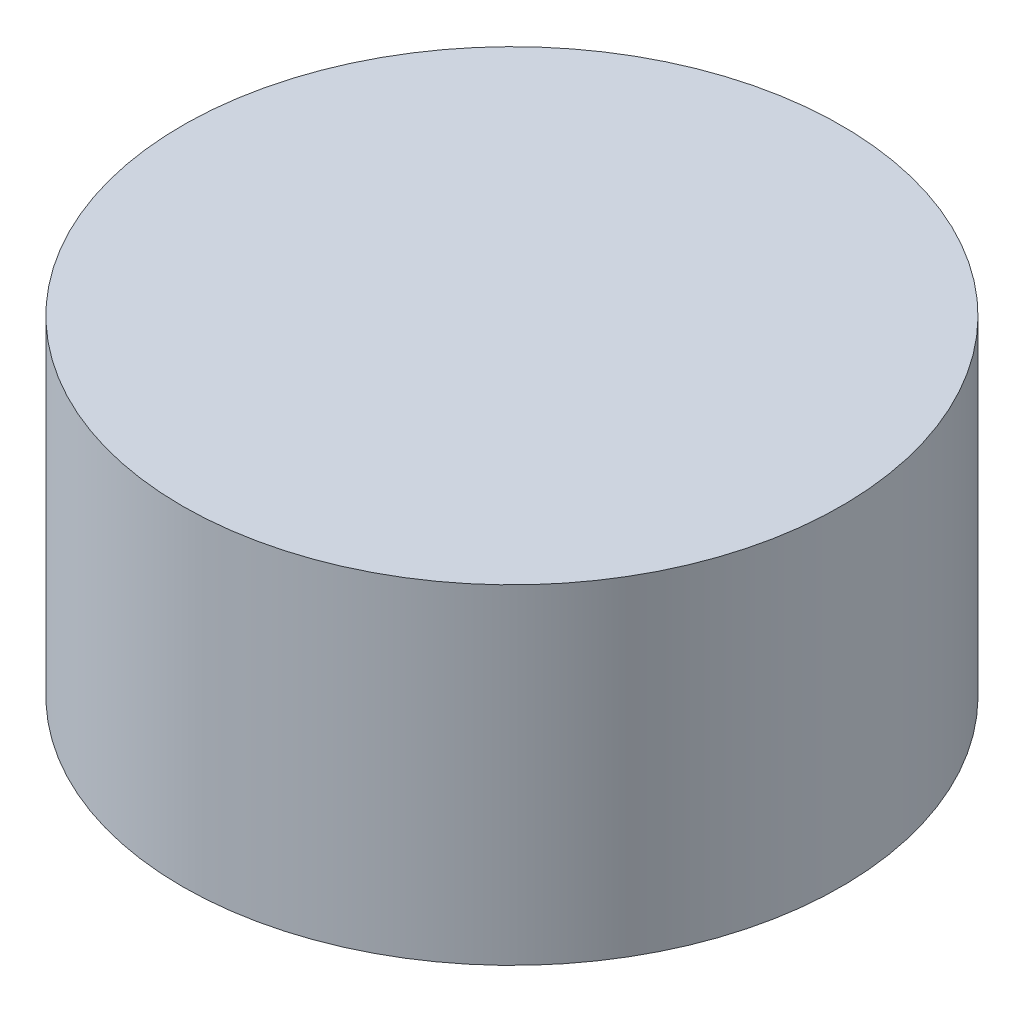
SolidWorks part; units mm, degrees
ref_plane "Front Plane" through (0, 0, 0) normal (0, 0, 1) x (1, 0, 0)
ref_plane "Top Plane" through (0, 0, 0) normal (0, 1, 0) x (1, 0, 0)
ref_plane "Right Plane" through (0, 0, 0) normal (1, 0, 0) x (0, 0, -1)
sketch "Sketch1" plane through (0, 0, 0) normal (0, 1, 0) x (1, 0, 0)
  circle A0 centre (0, 0) radius 4
  dimension "D1" = 8
extrude "Boss-Extrude1" add sketch "Sketch1" along normal blind 4
